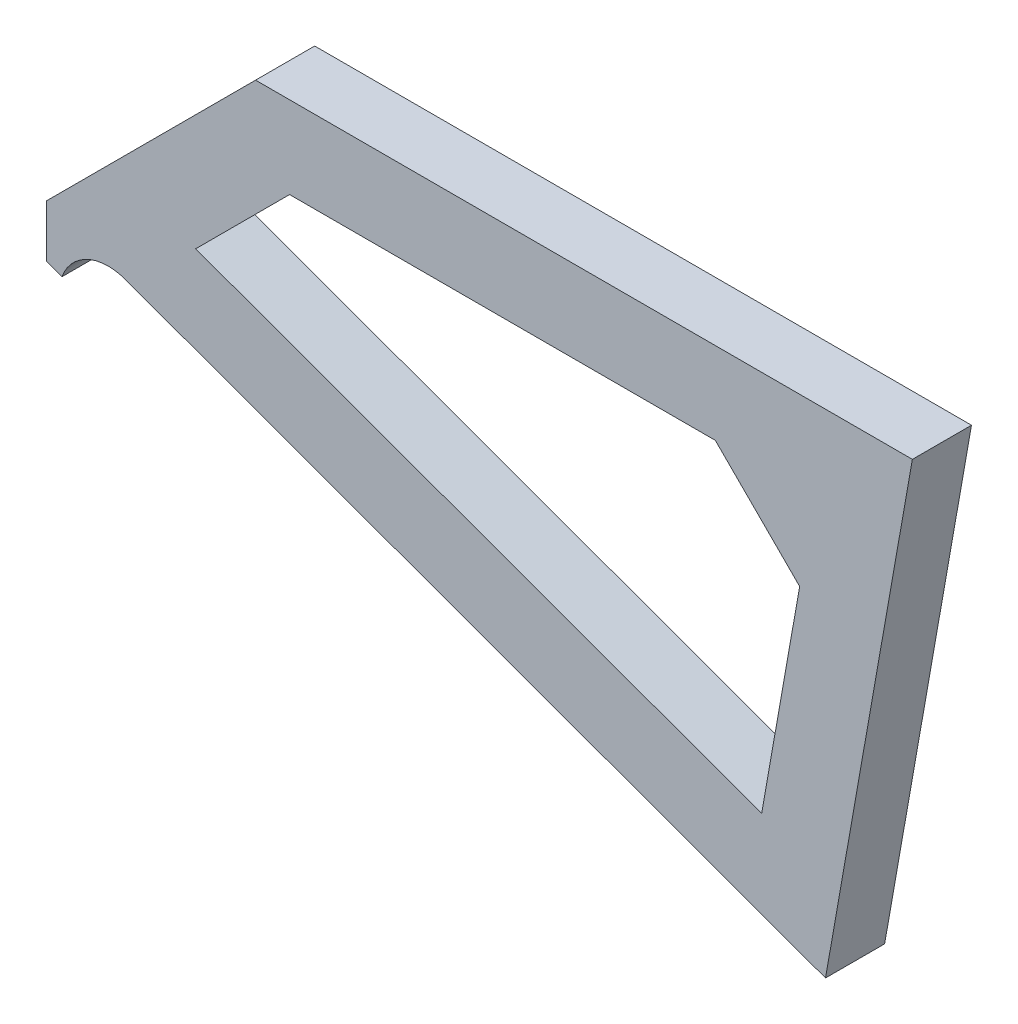
SolidWorks part; units mm, degrees
ref_plane "Front Plane" through (0, 0, 0) normal (0, 0, 1) x (1, 0, 0)
ref_plane "Top Plane" through (0, 0, 0) normal (0, 1, 0) x (1, 0, 0)
ref_plane "Right Plane" through (0, 0, 0) normal (1, 0, 0) x (0, 0, -1)
sketch "Sketch1" plane through (0, 0, 0) normal (0, 0, 1) x (-1, 0, 0)
  line L0 (263.6617, 63.6617) -> (200, 0)
  line L24 (263.6617, 63.6617) -> (26.449, 150)
  line L25 (26.449, 150) -> (0, 0)
  line L26 (0, 0) -> (200, 0)
  point P0 (0, 0)
  dimension "D1" = 80
  dimension "D2" = 150
  dimension "D3" = 20
  dimension "D4" = 200
  dimension "D5" = 45
sketch "Sketch4" plane through (0, 0, 0) normal (0, 0, 1) x (1, 0, 0)
  line L0 (-258.9632, -81.3344) -> (-263.6617, -79.6243)
  line L1 (-263.6617, -65.7327) -> (-263.6617, -79.6243)
  line L2 (-192.5736, -27.9289) -> (-207.1363, -42.4916)
  line L4 (-200, 0) -> (-263.6617, -63.6617)
  line L5 (-263.6617, -63.6617) -> (-26.449, -150)
  line L6 (-26.449, -150) -> (0, 0)
  line L7 (0, 0) -> (-200, 0)
  line L8 (-201.4645, -1.4645) -> (-262.1972, -62.1972)
  line L9 (-239.7375, -72.3693) -> (-32.0485, -147.962)
  line L10 (-25.4143, -144.1318) -> (-1.0347, -5.8682)
  line L11 (-5.9588, 0) -> (-197.9289, 0)
  line L13 (-203.4854, -58.9596) -> (-57.0944, -112.2416)
  line L14 (-43.8261, -104.5811) -> (-37.8573, -70.73)
  line L16 (-76.2293, -25) -> (-185.5025, -25)
  line L17 (-218.2356, -53.591) -> (-45.8956, -116.3176) construction
  line L18 (-29.7938, -25) -> (-189.6447, -25) construction
  line L19 (-45.8956, -116.3176) -> (-29.7938, -25) construction
  line L20 (-189.6447, -25) -> (-218.2356, -53.591) construction
  line L21 (-218.2356, -53.591) -> (-218.2356, -53.591) construction
  line L22 (-218.2356, -53.591) -> (-218.2356, -53.591) construction
  arc A1 (-239.7375, -72.3693) -> (-258.9632, -81.3344) centre (-244.8678, -86.4647) ccw
  circle A2 centre (-29.7938, -25) radius 12.5
  arc A3 (-262.1972, -62.1972) -> (-263.6617, -65.7327) centre (-258.6617, -65.7327) ccw
  arc A4 (-201.4645, -1.4645) -> (-197.9289, 0) centre (-197.9289, -5) cw
  arc A5 (-1.0347, -5.8682) -> (-5.9588, 0) centre (-5.9588, -5) ccw
  arc A6 (-32.0485, -147.962) -> (-25.4143, -144.1318) centre (-30.3384, -143.2635) ccw
  arc A10 (-29.7938, -25) -> (-29.7938, -25) centre (-29.7938, -25) ccw
  arc A12 (-66.4534, -32.8947) -> (-43.9345, -59.7317) centre (-29.7938, -25) ccw
  arc A13 (-66.4534, -32.8947) -> (-76.2293, -25) centre (-76.2293, -35) ccw
  circle A14 centre (-29.7938, -25) radius 37.5 construction
  arc A15 (-43.9345, -59.7317) -> (-37.8573, -70.73) centre (-47.7053, -68.9935) cw
  arc A16 (-43.8261, -104.5811) -> (-57.0944, -112.2416) centre (-53.6742, -102.8446) cw
  arc A17 (-45.8956, -116.3176) -> (-45.8956, -116.3176) centre (-45.8956, -116.3176) ccw construction
  arc A18 (-185.5025, -25) -> (-192.5736, -27.9289) centre (-185.5025, -35) ccw
  arc A19 (-189.6447, -25) -> (-189.6447, -25) centre (-189.6447, -25) cw construction
  arc A20 (-203.4854, -58.9596) -> (-207.1363, -42.4916) centre (-200.0652, -49.5627) cw
  arc A21 (-218.2356, -53.591) -> (-218.2356, -53.591) centre (-218.2356, -53.591) cw construction
  arc A22 (-218.2356, -53.591) -> (-218.2356, -53.591) centre (-218.2356, -53.591) ccw construction
  point P40 (7.7062, -25)
  dimension "D2" = 30
  dimension "D5" = 25
  dimension "D8" = 5
  dimension "D11" = 10
  dimension "D12" = 10
  dimension "D3" = 15
  dimension "D4" = 5
  dimension "D6" = 25
  dimension "D7" = 25
  dimension "D1" = 0
  dimension "D9" = 25
  dimension "D10" = 25
extrude "Boss-Extrude1" [suppressed] add sketch "Sketch4" along normal blind 18 contours L9 A6 L10 A5 L11 A4 L8 A3 L1 L0 A1 A2 L13 A20 L2 A18 L16 A13 A12 A15 L14 A16
sketch "Sketch5" plane through (0, 0, 0) normal (0, 0, 1) x (1, 0, 0)
  line L0 (-34.3216, -50.6784) -> (-60, -25)
  line L1 (-45.8956, -116.3176) -> (-34.3216, -50.6784)
  line L2 (-60, -25) -> (-189.6447, -25)
  line L3 (-189.6447, -25) -> (-218.2356, -53.591)
  line L4 (-218.2356, -53.591) -> (-218.2356, -53.591)
  line L6 (-239.7375, -72.3693) -> (-32.0485, -147.962)
  line L7 (-263.6617, -79.6243) -> (-258.9632, -81.3344)
  line L8 (-263.6617, -65.7327) -> (-263.6617, -79.6243)
  line L9 (-201.4645, -1.4645) -> (-262.1972, -62.1972)
  line L10 (-5.9588, 0) -> (-197.9289, 0)
  line L11 (-25.4143, -144.1318) -> (-1.0347, -5.8682)
  line L12 (-239.7375, -72.3693) -> (-32.0485, -147.962)
  line L13 (-263.6617, -79.6243) -> (-258.9632, -81.3344)
  line L14 (-263.6617, -65.7327) -> (-263.6617, -79.6243)
  line L15 (-201.4645, -1.4645) -> (-262.1972, -62.1972)
  line L16 (-5.9588, 0) -> (-197.9289, 0)
  line L17 (-25.4143, -144.1318) -> (-1.0347, -5.8682)
  line L24 (-218.2356, -53.591) -> (-218.2356, -53.591)
  line L25 (-218.2356, -53.591) -> (-45.8956, -116.3176)
  line L27 (-45.8956, -116.3176) -> (-29.7938, -25) construction
  line L28 (-29.7938, -25) -> (-189.6447, -25) construction
  line L31 (-197.9289, 0) -> (-200, 0)
  line L32 (-200, 0) -> (-201.4645, -1.4645)
  line L33 (-263.6617, -65.7327) -> (-263.6617, -63.6617)
  line L34 (-263.6617, -63.6617) -> (-262.1972, -62.1972)
  line L35 (-32.0485, -147.962) -> (-26.449, -150)
  line L36 (-26.449, -150) -> (-25.4143, -144.1318)
  line L37 (-1.0347, -5.8682) -> (0, 0)
  line L38 (0, 0) -> (-5.9588, 0)
  arc A0 (-29.7938, -25) -> (-29.7938, -25) centre (-29.7938, -25) ccw
  arc A1 (-189.6447, -25) -> (-189.6447, -25) centre (-189.6447, -25) ccw
  arc A3 (-218.2356, -53.591) -> (-218.2356, -53.591) centre (-218.2356, -53.591) ccw
  arc A4 (-218.2356, -53.591) -> (-218.2356, -53.591) centre (-218.2356, -53.591) cw
  arc A5 (-45.8956, -116.3176) -> (-45.8956, -116.3176) centre (-45.8956, -116.3176) ccw
  arc A7 (-239.7375, -72.3693) -> (-258.9632, -81.3344) centre (-244.8678, -86.4647) ccw
  arc A8 (-262.1972, -62.1972) -> (-263.6617, -65.7327) centre (-258.6617, -65.7327) ccw
  arc A9 (-197.9289, 0) -> (-201.4645, -1.4645) centre (-197.9289, -5) ccw
  arc A10 (-1.0347, -5.8682) -> (-5.9588, 0) centre (-5.9588, -5) ccw
  arc A11 (-32.0485, -147.962) -> (-25.4143, -144.1318) centre (-30.3384, -143.2635) ccw
  arc A12 (-239.7375, -72.3693) -> (-258.9632, -81.3344) centre (-244.8678, -86.4647) ccw
  arc A33 (-197.9289, 0) -> (-201.4645, -1.4645) centre (-197.9289, -5) ccw construction
  arc A34 (-262.1972, -62.1972) -> (-263.6617, -65.7327) centre (-258.6617, -65.7327) ccw construction
  arc A35 (-32.0485, -147.962) -> (-25.4143, -144.1318) centre (-30.3384, -143.2635) ccw construction
  arc A36 (-1.0347, -5.8682) -> (-5.9588, 0) centre (-5.9588, -5) ccw construction
  dimension "D1" = 45
  dimension "D4" = 60
  dimension "D2" = 0
  dimension "D3" = 25
extrude "Boss-Extrude2" add sketch "Sketch5" along normal blind 18 contours A12 L12 L35 L36 L17 L37 L38 L16 L31 L32 L15 L34 L33 L14 L13 L25 L3 L2 L0 L1
